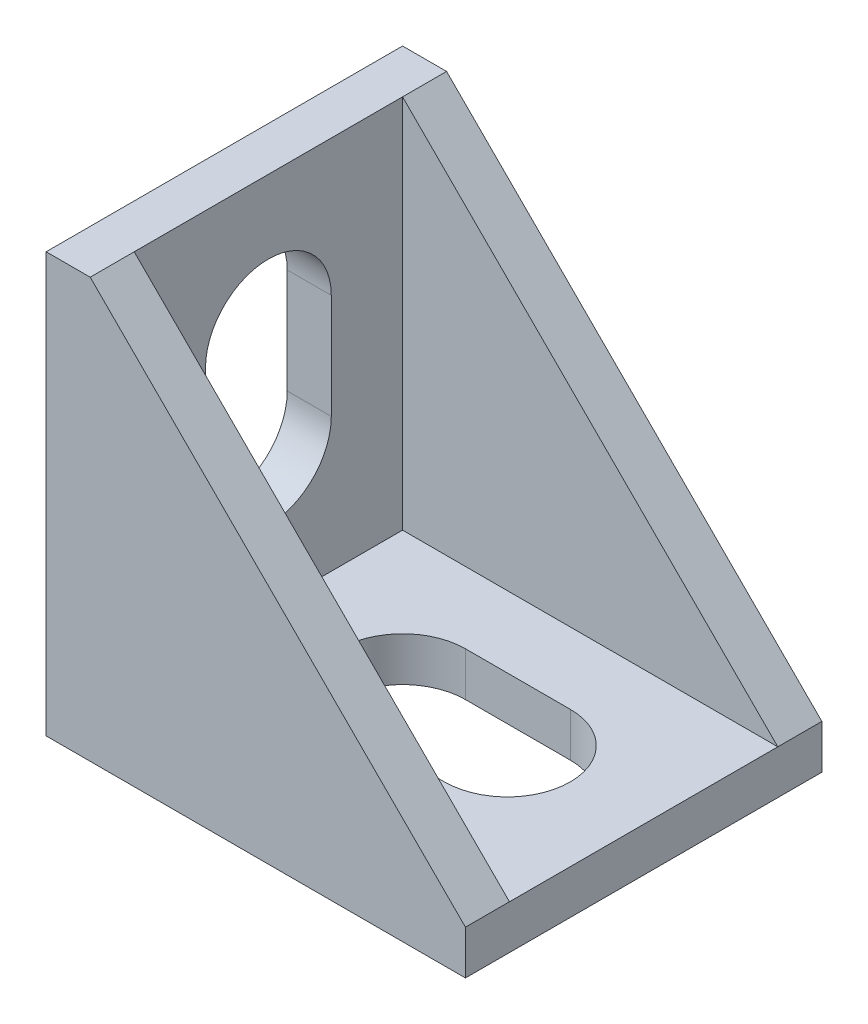
SolidWorks part; units mm, degrees
ref_plane "前视基准面" through (0, 0, 0) normal (0, 0, 1) x (1, 0, 0)
ref_plane "上视基准面" through (0, 0, 0) normal (0, 1, 0) x (1, 0, 0)
ref_plane "右视基准面" through (0, 0, 0) normal (1, 0, 0) x (0, 0, -1)
sketch "草图1" plane through (0, 0, 0) normal (0, 0, 1) x (1, 0, 0)
  line L0 (0, 0) -> (20, 0)
  line L1 (20, 0) -> (20, 2.1)
  line L2 (20, 2.1) -> (2.1, 2.1)
  line L3 (2.1, 2.1) -> (2.1, 20)
  line L4 (2.1, 20) -> (0, 20)
  line L5 (0, 20) -> (0, 0)
  dimension "D1" = 20
  dimension "D2" = 20
  dimension "D3" = 2.1
  dimension "D4" = 2.1
extrude "凸台-拉伸1" add sketch "草图1" along normal blind 17
sketch "草图2" plane through (0, 0, 0) normal (0, 0, -1) x (-1, 0, 0)
  line L0 (-2.1, 20) -> (-2.1, 2.1)
  line L1 (-2.1, 2.1) -> (-20, 2.1)
  line L2 (-20, 2.1) -> (-2.1, 20)
extrude "凸台-拉伸2" add sketch "草图2" against normal blind 2.1
sketch "草图3" plane through (0, 0, 17) normal (0, 0, 1) x (1, 0, 0)
  line L0 (2.1, 20) -> (2.1, 2.1)
  line L1 (2.1, 2.1) -> (20, 2.1)
  line L2 (20, 2.1) -> (2.1, 20)
extrude "凸台-拉伸3" add sketch "草图3" against normal blind 2.1
sketch "草图4" plane through (2.1, 0, 0) normal (1, 0, 0) x (0, 0, -1)
  line L0 (-14.9, 2.1) -> (-2.1, 2.1) construction
  line L1 (-11.5, 13.5) -> (-11.5, 8.5)
  line L2 (-5.5, 13.5) -> (-5.5, 8.5)
  arc A0 (-11.5, 8.5) -> (-5.5, 8.5) centre (-8.5, 8.5) ccw
  arc A1 (-5.5, 13.5) -> (-11.5, 13.5) centre (-8.5, 13.5) ccw
  dimension "D1" = 6.4
  dimension "D2" = 5
extrude "切除-拉伸1" cut sketch "草图4" against normal through all
sketch "草图5" plane through (0, 2.1, 0) normal (0, 1, 0) x (1, 0, 0)
  line L0 (2.1, -14.9) -> (2.1, -2.1) construction
  line L1 (8.5, -11.5) -> (13.5, -11.5)
  line L3 (13.5, -5.5) -> (8.5, -5.5)
  arc A1 (13.5, -11.5) -> (13.5, -5.5) centre (13.5, -8.5) ccw
  arc A3 (8.5, -5.5) -> (8.5, -11.5) centre (8.5, -8.5) ccw
  dimension "D1" = 6.4
  dimension "D2" = 5
extrude "切除-拉伸2" cut sketch "草图5" against normal through all
